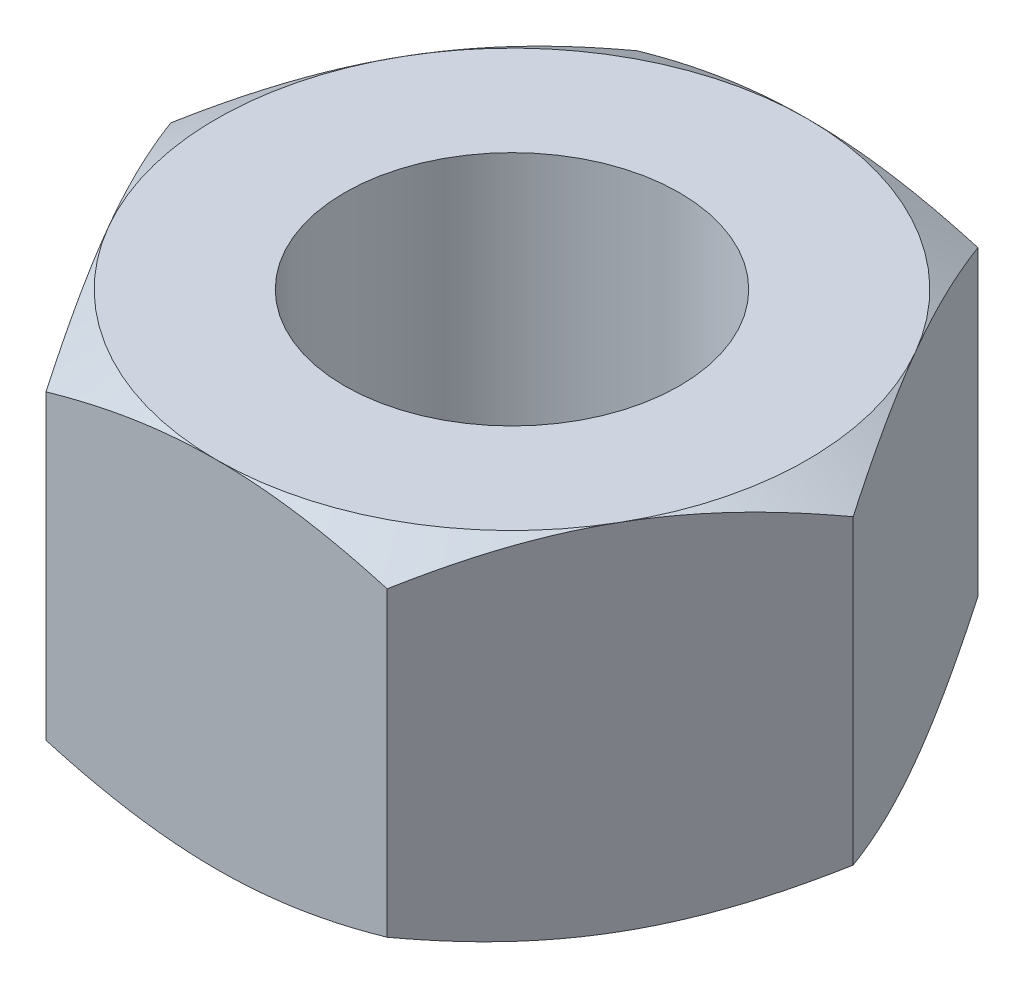
SolidWorks part; units mm, degrees
material "Chrome Stainless Steel"
ref_plane "Front Plane" through (0, 0, 0) normal (0, 0, 1) x (1, 0, 0)
ref_plane "Top Plane" through (0, 0, 0) normal (0, 1, 0) x (1, 0, 0)
ref_plane "Right Plane" through (0, 0, 0) normal (1, 0, 0) x (0, 0, -1)
sketch "Sketch1" plane through (0, 0, 0) normal (0, 1, 0) x (1, 0, 0)
  line L1 (10.3923, 0) -> (5.1962, 9)
  line L2 (5.1962, 9) -> (-5.1962, 9)
  line L3 (-5.1962, 9) -> (-10.3923, 0)
  line L4 (-10.3923, 0) -> (-5.1962, -9)
  line L5 (-5.1962, -9) -> (5.1962, -9)
  line L6 (5.1962, -9) -> (10.3923, 0)
  circle A0 centre (0, 0) radius 9 construction
  dimension "D1" = 18
extrude "Boss-Extrude1" add sketch "Sketch1" along normal mid plane 10.8
sketch "Sketch2" plane through (0, 0, 0) normal (1, 0, 0) x (0, 0, -1)
  line L0 (0, 0) -> (0, -50000) construction
  line L1 (9, 5.4) -> (13.8136, 5.4)
  line L2 (13.8136, 5.4) -> (13.8136, 2.6209)
  line L3 (13.8136, 2.6209) -> (9, 5.4)
  dimension "D1" = 30
revolve "Cut-Revolve1" cut sketch "Sketch2" angle 360 about L0
mirror "Mirror1" about plane through (0, 0, 0) normal (0, 1, 0) of "Cut-Revolve1"
hole_wizard "M12x1.75 Tapped Hole1" positions "Sketch3" profile "Sketch4" tap size "M12x1.75" standard "ANSI Metric" end condition up to next
sketch "Sketch3" plane through (0, 5.4, 0) normal (0, 1, 0) x (1, 0, 0)
  point P0 (0, 0)
sketch "Sketch4" plane through (0, 5.4, 0) normal (1, 0, 0) x (0, 0, 1)
  line L0 (0, 0) -> (0, 10.8)
  line L1 (0, 10.8) -> (5.1, 10.8)
  line L2 (5.1, 10.8) -> (5.1, 0)
  line L5 (5.1, 0) -> (0, 0)
  line L11 (0, -6.35) -> (0, 107.95) construction
  dimension "Thru Tap Drill Dia." = 10.2
  dimension "Thru Tap Drill Depth" = 10.8
cosmetic thread "Hole Thread1" parameters "D2"=12
